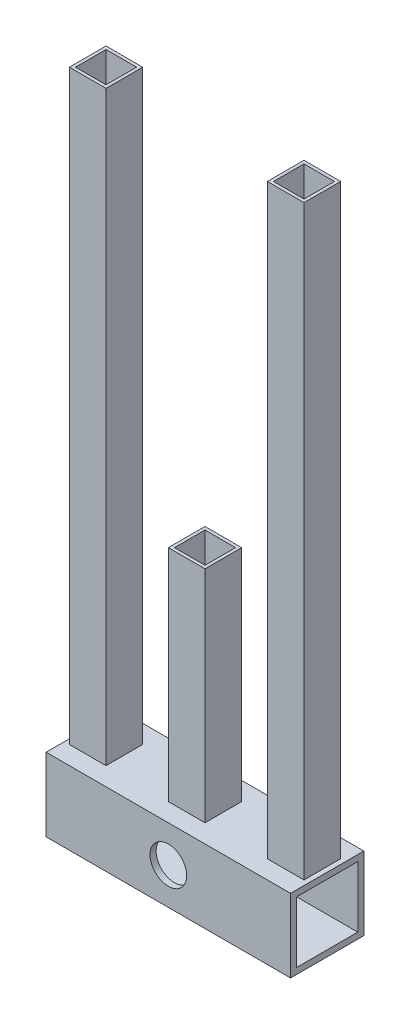
SolidWorks part; units mm, degrees
ref_plane "Front Plane" through (0, 0, 0) normal (0, 0, 1) x (1, 0, 0)
ref_plane "Top Plane" through (0, 0, 0) normal (0, 1, 0) x (1, 0, 0)
ref_plane "Right Plane" through (0, 0, 0) normal (1, 0, 0) x (0, 0, -1)
sketch "Sketch1" plane through (0, 0, 0) normal (1, 0, 0) x (0, 0, -1)
  line L1 (-15.875, -15.875) -> (15.875, -15.875)
  line L2 (-15.875, -15.875) -> (-15.875, 15.875)
  line L3 (-15.875, 15.875) -> (15.875, 15.875)
  line L4 (15.875, -15.875) -> (15.875, 15.875)
  line L5 (-15.875, -15.875) -> (15.875, 15.875) construction
  line L6 (-15.875, 15.875) -> (15.875, -15.875) construction
  line L7 (-19.05, -19.05) -> (19.05, -19.05)
  line L8 (-19.05, -19.05) -> (-19.05, 19.05)
  line L9 (-19.05, 19.05) -> (19.05, 19.05)
  line L10 (19.05, -19.05) -> (19.05, 19.05)
  line L11 (-19.05, -19.05) -> (19.05, 19.05) construction
  line L12 (-19.05, 19.05) -> (19.05, -19.05) construction
  point P0 (0, 0)
  point P6 (0, 0)
  dimension "D1" = 38.1
  dimension "D2" = 3.175
extrude "Boss-Extrude1" add sketch "Sketch1" along normal blind 127
sketch "Sketch2" plane through (0, 19.05, 0) normal (0, 1, 0) x (1, 0, 0)
  line L0 (127, 19.05) -> (0, 19.05) construction
  line L1 (55.5625, 7.9375) -> (71.4375, 7.9375)
  line L2 (55.5625, 7.9375) -> (55.5625, -7.9375)
  line L3 (55.5625, -7.9375) -> (71.4375, -7.9375)
  line L4 (71.4375, 7.9375) -> (71.4375, -7.9375)
  line L5 (55.5625, 7.9375) -> (71.4375, -7.9375) construction
  line L6 (55.5625, -7.9375) -> (71.4375, 7.9375) construction
  line L7 (53.975, -9.525) -> (73.025, -9.525)
  line L8 (53.975, -9.525) -> (53.975, 9.525)
  line L9 (53.975, 9.525) -> (73.025, 9.525)
  line L10 (73.025, -9.525) -> (73.025, 9.525)
  line L11 (53.975, -9.525) -> (73.025, 9.525) construction
  line L12 (53.975, 9.525) -> (73.025, -9.525) construction
  point P0 (63.5, 0)
  point P5 (63.5, 0)
  point P13 (63.5, 19.05)
  dimension "D1" = 19.05
  dimension "D2" = 1.5875
extrude "Boss-Extrude2" add sketch "Sketch2" along normal blind 114.3
sketch "Sketch3" plane through (0, 19.05, 0) normal (0, 1, 0) x (1, 0, 0)
  line L1 (4.1275, -7.9375) -> (20.0025, -7.9375)
  line L2 (4.1275, -7.9375) -> (4.1275, 7.9375)
  line L3 (4.1275, 7.9375) -> (20.0025, 7.9375)
  line L4 (20.0025, -7.9375) -> (20.0025, 7.9375)
  line L5 (4.1275, -7.9375) -> (20.0025, 7.9375) construction
  line L6 (4.1275, 7.9375) -> (20.0025, -7.9375) construction
  line L7 (2.54, -9.525) -> (21.59, -9.525)
  line L8 (2.54, -9.525) -> (2.54, 9.525)
  line L9 (2.54, 9.525) -> (21.59, 9.525)
  line L10 (21.59, -9.525) -> (21.59, 9.525)
  line L11 (2.54, -9.525) -> (21.59, 9.525) construction
  line L12 (2.54, 9.525) -> (21.59, -9.525) construction
  point P0 (12.065, 0)
  point P5 (12.065, 0)
  dimension "D1" = 19.05
  dimension "D2" = 1.5875
  dimension "D3" = 2.54
extrude "Boss-Extrude3" add sketch "Sketch3" along normal blind 304.8
ref_plane "Plane1" through (63.5, 0, 0) normal (-1, 0, 0) x (0, 0, 1)
mirror "Mirror1" about plane through (63.5, 0, 0) normal (-1, 0, 0) of "Boss-Extrude3"
sketch "Sketch4" plane through (0, 0, 19.05) normal (0, 0, 1) x (1, 0, 0)
  line L0 (63.5, 20.955) -> (63.5, -20.955) construction
  circle A0 centre (63.5, 0) radius 9.525
  dimension "D1" = 19.05
extrude "Cut-Extrude1" cut sketch "Sketch4" against normal through all
